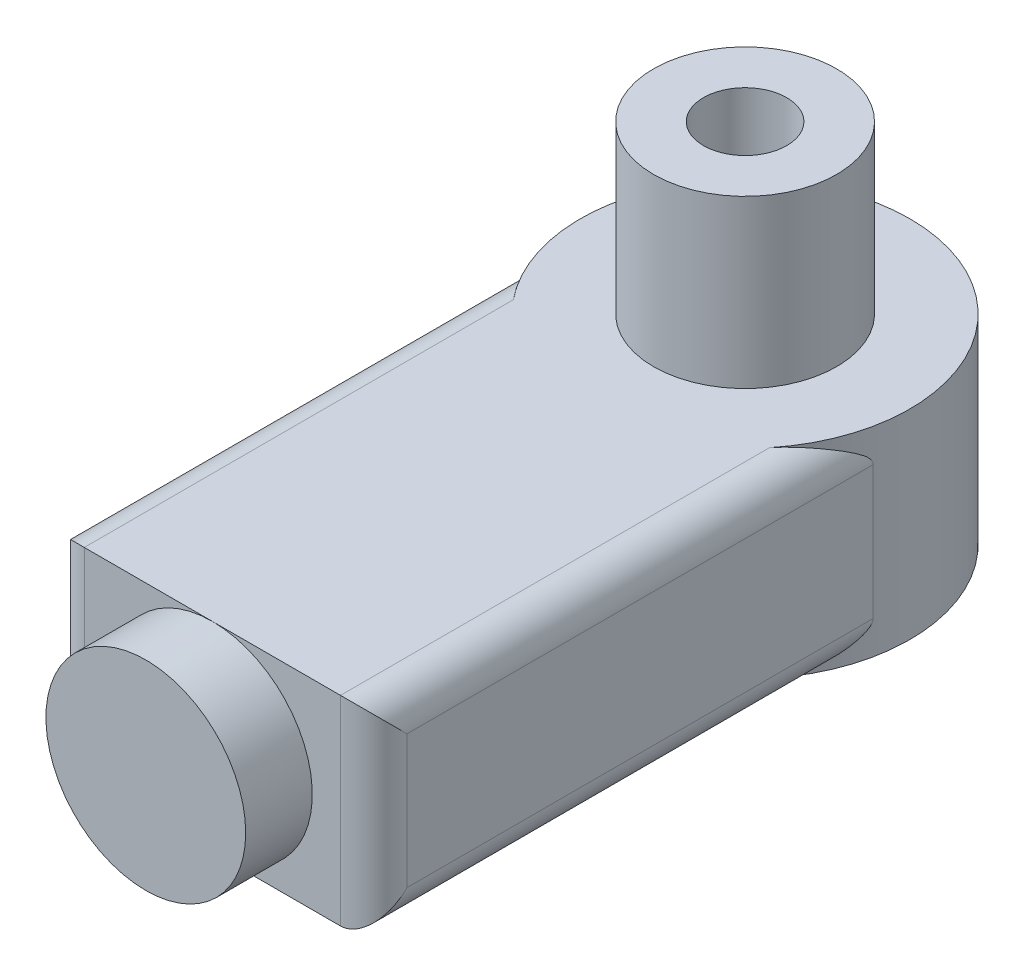
SolidWorks part; units mm, degrees
material "ABS"
ref_plane "前视基准面" through (0, 0, 0) normal (0, 0, 1) x (1, 0, 0)
ref_plane "上视基准面" through (0, 0, 0) normal (0, 1, 0) x (1, 0, 0)
ref_plane "右视基准面" through (0, 0, 0) normal (1, 0, 0) x (0, 0, -1)
sketch "草图1" plane through (0, 0, 0) normal (0, 1, 0) x (1, 0, 0)
  line L2 (-4.8474, -1) -> (-4.8474, -16)
  line L3 (-4.8474, -16) -> (4.8474, -16)
  line L4 (4.8474, -1) -> (4.8474, -16)
  arc A0 (4.8474, -1) -> (-4.8474, -1) centre (0, 0) ccw
  dimension "D2" = 15
extrude "凸台-拉伸1" add sketch "草图1" along normal blind 6 contours A0 L2 L3 L4
sketch "草图2" plane through (0, 6, 0) normal (0, 1, 0) x (1, 0, 0)
  circle A0 centre (0, 0) radius 2.75
  circle A1 centre (0, 0) radius 1.25
extrude "凸台-拉伸2" add sketch "草图2" along normal blind 5 separate body
sketch "草图3" plane through (0, 0, 16) normal (0, 0, 1) x (1, 0, 0)
  circle A0 centre (0, 3) radius 3
extrude "凸台-拉伸3" add sketch "草图3" along normal blind 2
fillet "圆角1" radius 1 6 edges at (-4.8474, 3, 16) (4.8474, 3, 16) (-4.8474, 6, 8.5) (-4.8474, 0, 8.5) (4.8474, 6, 8.5) (4.8474, 0, 8.5)
